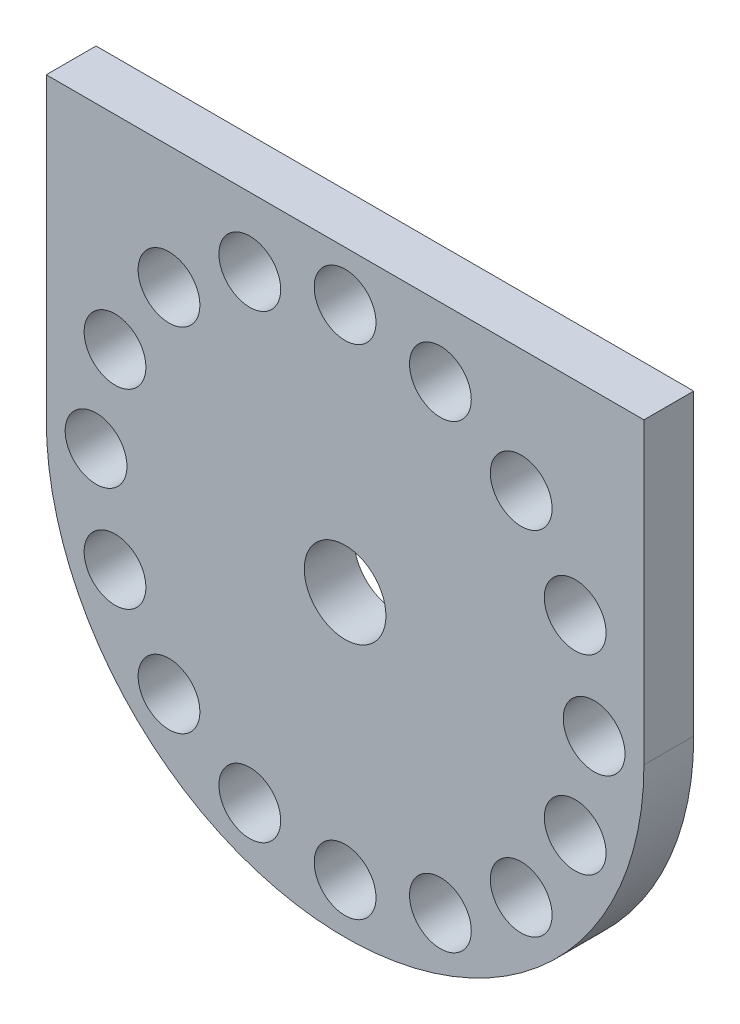
SolidWorks part; units mm, degrees
ref_plane "前视基准面" through (0, 0, 0) normal (0, 0, 1) x (1, 0, 0)
ref_plane "上视基准面" through (0, 0, 0) normal (0, 1, 0) x (1, 0, 0)
ref_plane "右视基准面" through (0, 0, 0) normal (1, 0, 0) x (0, 0, -1)
sketch "草图2" plane through (0, 0, 0) normal (0, 0, 1) x (1, 0, 0)
  line L1 (-30, 30) -> (30, 30)
  line L2 (-30, 30) -> (-30, 0)
  line L4 (30, 30) -> (30, 0)
  line L5 (-30, 30) -> (21.2132, -21.2132) construction
  line L6 (-21.2132, -21.2132) -> (30, 30) construction
  arc A0 (-30, 0) -> (30, 0) centre (0, 0) ccw
extrude "凸台-拉伸1" add sketch "草图2" along normal blind 5
sketch "草图3" plane through (0, 0, 5) normal (0, 0, 1) x (1, 0, 0)
  circle A0 centre (0, 0) radius 4.1
extrude "切除-拉伸1" cut sketch "草图3" against normal blind 5
sketch "草图5" plane through (0, 0, 5) normal (0, 0, 1) x (1, 0, 0)
  circle A0 centre (0, 25) radius 3.1
  circle A1 centre (0, 0) radius 4.1 construction
  circle A2 centre (9.5671, 23.097) radius 3.1
  circle A3 centre (17.6777, 17.6777) radius 3.1
  circle A4 centre (23.097, 9.5671) radius 3.1
  circle A5 centre (25, 0) radius 3.1
  circle A6 centre (23.097, -9.5671) radius 3.1
  circle A7 centre (17.6777, -17.6777) radius 3.1
  circle A8 centre (9.5671, -23.097) radius 3.1
  circle A9 centre (0, -25) radius 3.1
  circle A10 centre (-9.5671, -23.097) radius 3.1
  circle A11 centre (-17.6777, -17.6777) radius 3.1
  circle A12 centre (-23.097, -9.5671) radius 3.1
  circle A13 centre (-25, 0) radius 3.1
  circle A14 centre (-23.097, 9.5671) radius 3.1
  circle A15 centre (-17.6777, 17.6777) radius 3.1
  circle A16 centre (-9.5671, 23.097) radius 3.1
  point P38 (0, 0)
  dimension "D1" = 25
  dimension "D3" = 6.2
  dimension "D2" = 16
extrude "切除-拉伸2" cut sketch "草图5" against normal blind 5
